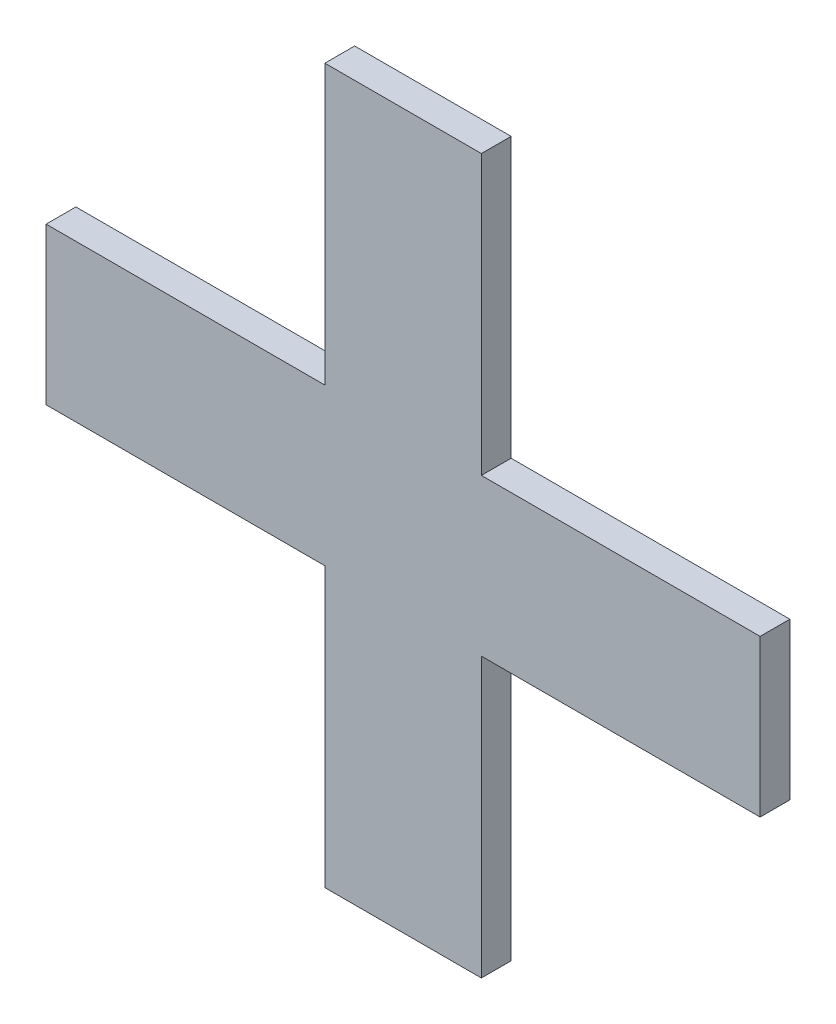
SolidWorks part; units mm, degrees
ref_plane "Front Plane" through (0, 0, 0) normal (0, 0, 1) x (1, 0, 0)
ref_plane "Top Plane" through (0, 0, 0) normal (0, 1, 0) x (1, 0, 0)
ref_plane "Right Plane" through (0, 0, 0) normal (1, 0, 0) x (0, 0, -1)
sketch "Sketch1" plane through (0, 0, 0) normal (0, 0, 1) x (1, 0, 0)
  line L1 (-60, 13.15) -> (60, 13.15)
  line L2 (-60, 13.15) -> (-60, -13.15)
  line L3 (-60, -13.15) -> (60, -13.15)
  line L4 (60, 13.15) -> (60, -13.15)
  line L5 (-60, 13.15) -> (60, -13.15) construction
  line L6 (-60, -13.15) -> (60, 13.15) construction
  line L7 (-13.15, -60) -> (13.15, -60)
  line L8 (-13.15, -60) -> (-13.15, 60)
  line L9 (-13.15, 60) -> (13.15, 60)
  line L10 (13.15, -60) -> (13.15, 60)
  line L11 (-13.15, -60) -> (13.15, 60) construction
  line L12 (-13.15, 60) -> (13.15, -60) construction
  point P0 (0, 0)
  point P6 (0, 0)
  dimension "D1" = 26.3
  dimension "D2" = 26.3
  dimension "D3" = 120
  dimension "D4" = 120
extrude "Boss-Extrude1" add sketch "Sketch1" along normal blind 5 contours L3 L8 L1 L2 | L3 L10 L1 L8 | L10 L3 L4 L1 | L7 L10 L3 L8 | L1 L10 L9 L8
